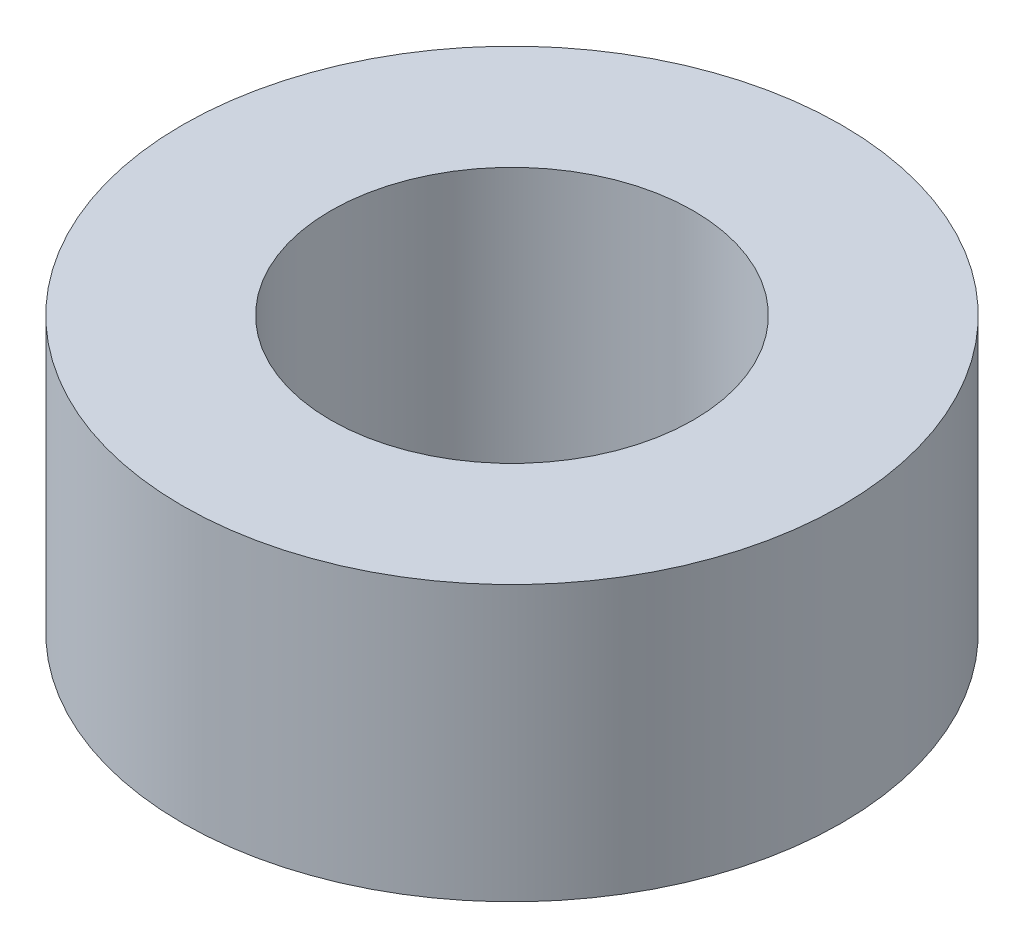
SolidWorks part; units mm, degrees
ref_plane "Front Plane" through (0, 0, 0) normal (0, 0, 1) x (1, 0, 0)
ref_plane "Top Plane" through (0, 0, 0) normal (0, 1, 0) x (1, 0, 0)
ref_plane "Right Plane" through (0, 0, 0) normal (1, 0, 0) x (0, 0, -1)
sketch "Sketch1" plane through (0, 0, 0) normal (0, 1, 0) x (1, 0, 0)
  circle A0 centre (0, 0) radius 1.65
  circle A1 centre (0, 0) radius 3
extrude "Boss-Extrude1" add sketch "Sketch1" along normal blind 2.5
